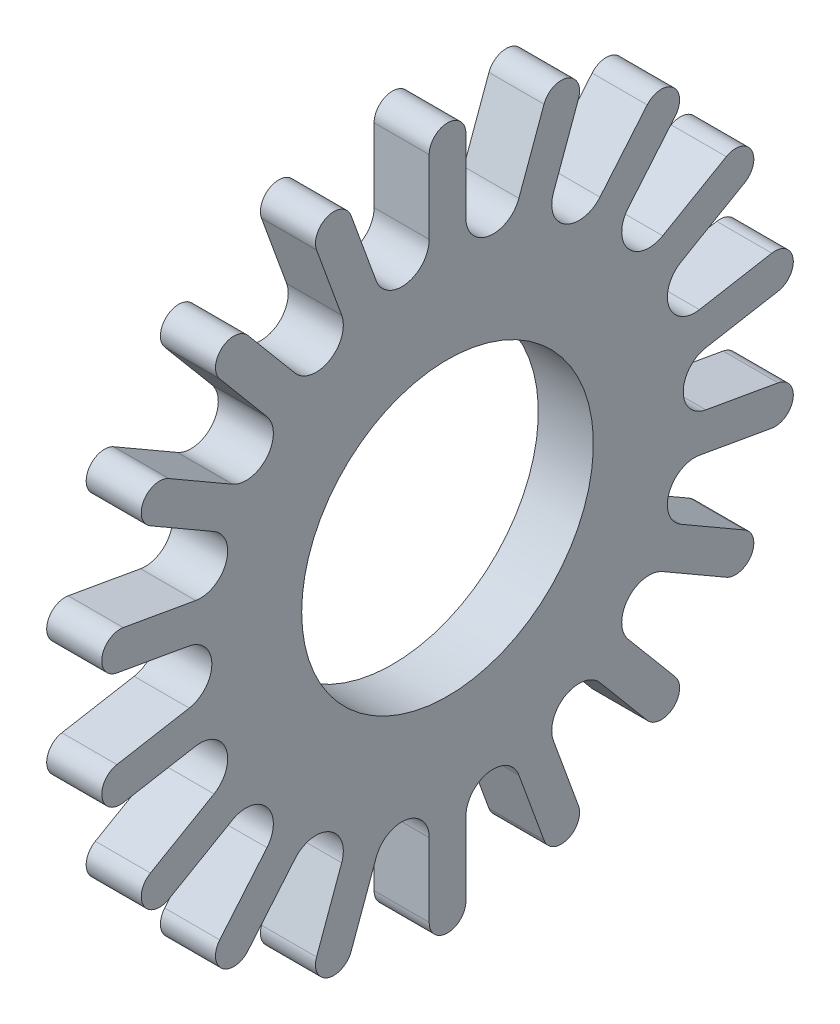
SolidWorks part; units mm, degrees
ref_plane "Front Plane" through (0, 0, 0) normal (0, 0, 1) x (1, 0, 0)
ref_plane "Top Plane" through (0, 0, 0) normal (0, 1, 0) x (1, 0, 0)
ref_plane "Right Plane" through (0, 0, 0) normal (1, 0, 0) x (0, 0, -1)
sketch "Sketch1" plane through (0, 0, 0) normal (1, 0, 0) x (0, 0, -1)
  line L0 (6.9829, 40.646) -> (4.811, 34.6789)
  line L1 (9.9664, 39.5601) -> (7.7946, 33.593)
  line L2 (-2.9472, 41.8371) -> (-2.9472, 35.4871)
  line L4 (0.2278, 41.8371) -> (0.2278, 35.4871)
  line L6 (15.9067, 36.1304) -> (11.825, 31.2661)
  line L7 (18.3389, 34.0896) -> (14.2572, 29.2252)
  line L9 (22.7479, 28.8351) -> (17.2486, 25.6601)
  line L10 (24.3354, 26.0855) -> (18.8361, 22.9105)
  line L12 (26.6814, 19.6399) -> (20.4279, 18.5372)
  line L13 (27.2327, 16.5131) -> (20.9792, 15.4105)
  line L15 (27.2327, 9.6539) -> (20.9792, 10.7565)
  line L16 (26.6814, 6.5271) -> (20.4279, 7.6298)
  line L18 (24.3354, 0.0815) -> (18.8361, 3.2565)
  line L19 (22.7479, -2.6681) -> (17.2486, 0.5069)
  line L21 (18.3389, -7.9226) -> (14.2572, -3.0582)
  line L22 (15.9067, -9.9635) -> (11.825, -5.0991)
  line L24 (9.9664, -13.3931) -> (7.7946, -7.426)
  line L25 (6.9829, -14.479) -> (4.811, -8.5119)
  line L27 (0.2278, -15.6701) -> (0.2278, -9.3201)
  line L28 (-2.9472, -15.6701) -> (-2.9472, -9.3201)
  line L30 (-9.7022, -14.479) -> (-7.5304, -8.5119)
  line L31 (-12.6858, -13.3931) -> (-10.5139, -7.426)
  line L33 (-18.626, -9.9635) -> (-14.5443, -5.0991)
  line L34 (-21.0582, -7.9226) -> (-16.9765, -3.0582)
  line L36 (-25.4673, -2.6681) -> (-19.968, 0.5069)
  line L37 (-27.0548, 0.0815) -> (-21.5555, 3.2565)
  line L39 (-29.4008, 6.5271) -> (-23.1472, 7.6298)
  line L40 (-29.9521, 9.6539) -> (-23.6986, 10.7565)
  line L42 (-29.9521, 16.5131) -> (-23.6986, 15.4105)
  line L43 (-29.4008, 19.6399) -> (-23.1472, 18.5372)
  line L45 (-27.0548, 26.0855) -> (-21.5555, 22.9105)
  line L46 (-25.4673, 28.8351) -> (-19.968, 25.6601)
  line L48 (-21.0582, 34.0896) -> (-16.9765, 29.2252)
  line L49 (-18.626, 36.1304) -> (-14.5443, 31.2661)
  line L51 (-12.6858, 39.5601) -> (-10.5139, 33.593)
  line L52 (-9.7022, 40.646) -> (-7.5304, 34.6789)
  line L54 (-17.7064, 25.7882) -> (-15.2742, 27.8291) [skipped]
  line L55 (-12.3753, 30.6129) -> (-9.3917, 31.6988) [skipped]
  line L56 (-5.7155, 33.3233) -> (-2.5405, 33.3233) [skipped]
  line L57 (1.4696, 33.5925) -> (4.4531, 32.5066) [skipped]
  line L58 (8.3135, 31.388) -> (10.7457, 29.3471) [skipped]
  line L59 (13.9906, 26.9757) -> (15.5781, 24.2261) [skipped]
  line L60 (17.8163, 20.8878) -> (18.3676, 17.761) [skipped]
  line L61 (19.329, 13.8585) -> (18.7777, 10.7318) [skipped]
  line L62 (18.3464, 6.7358) -> (16.7589, 3.9862) [skipped]
  line L63 (14.987, 0.3788) -> (12.5548, -1.6621) [skipped]
  line L64 (9.6559, -4.4459) -> (6.6724, -5.5319) [skipped]
  line L65 (2.9962, -7.1563) -> (-0.1788, -7.1563) [skipped]
  line L66 (-4.189, -7.4255) -> (-7.1725, -6.3396) [skipped]
  line L67 (-11.0328, -5.221) -> (-13.465, -3.1802) [skipped]
  line L68 (-16.71, -0.8087) -> (-18.2975, 1.9409) [skipped]
  line L69 (-20.5357, 5.2792) -> (-21.087, 8.406) [skipped]
  line L70 (-22.0484, 12.3084) -> (-21.4971, 15.4352) [skipped]
  line L71 (-21.0658, 19.4311) -> (-19.4783, 22.1808) [skipped]
  circle A0 centre (-1.3597, 13.0835) radius 30.3411 construction
  arc A1 (-2.9472, 41.8371) -> (0.2278, 41.8371) centre (-1.3597, 41.8371) cw
  arc A2 (6.9829, 40.646) -> (9.9664, 39.5601) centre (8.4746, 40.103) cw
  arc A3 (15.9067, 36.1304) -> (18.3389, 34.0896) centre (17.1228, 35.11) cw
  arc A4 (22.7479, 28.8351) -> (24.3354, 26.0855) centre (23.5416, 27.4603) cw
  arc A5 (26.6814, 19.6399) -> (27.2327, 16.5131) centre (26.9571, 18.0765) cw
  arc A6 (27.2327, 9.6539) -> (26.6814, 6.5271) centre (26.9571, 8.0905) cw
  arc A7 (24.3354, 0.0815) -> (22.7479, -2.6681) centre (23.5416, -1.2933) cw
  arc A8 (18.3389, -7.9226) -> (15.9067, -9.9635) centre (17.1228, -8.943) cw
  arc A9 (9.9664, -13.3931) -> (6.9829, -14.479) centre (8.4746, -13.936) cw
  arc A10 (0.2278, -15.6701) -> (-2.9472, -15.6701) centre (-1.3597, -15.6701) cw
  arc A11 (-9.7022, -14.479) -> (-12.6858, -13.3931) centre (-11.194, -13.936) cw
  arc A12 (-18.626, -9.9635) -> (-21.0582, -7.9226) centre (-19.8421, -8.943) cw
  arc A13 (-25.4673, -2.6681) -> (-27.0548, 0.0815) centre (-26.261, -1.2933) cw
  arc A14 (-29.4008, 6.5271) -> (-29.9521, 9.6539) centre (-29.6764, 8.0905) cw
  arc A15 (-29.9521, 16.5131) -> (-29.4008, 19.6399) centre (-29.6764, 18.0765) cw
  arc A16 (-27.0548, 26.0855) -> (-25.4673, 28.8351) centre (-26.261, 27.4603) cw
  arc A17 (-21.0582, 34.0896) -> (-18.626, 36.1304) centre (-19.8421, 35.11) cw
  arc A18 (-12.6858, 39.5601) -> (-9.7022, 40.646) centre (-11.194, 40.103) cw
  arc A19 (4.811, 34.6789) -> (0.2278, 35.4871) centre (2.5907, 35.4871) cw
  arc A20 (11.825, 31.2661) -> (7.7946, 33.593) centre (10.0149, 32.7849) cw
  arc A21 (17.2486, 25.6601) -> (14.2572, 29.2252) centre (16.0672, 27.7064) cw
  arc A22 (20.4279, 18.5372) -> (18.8361, 22.9105) centre (20.0176, 20.8642) cw
  arc A23 (20.9792, 10.7565) -> (20.9792, 15.4105) centre (21.3895, 13.0835) cw
  arc A24 (18.8361, 3.2565) -> (20.4279, 7.6298) centre (20.0176, 5.3028) cw
  arc A25 (14.2572, -3.0582) -> (17.2486, 0.5069) centre (16.0672, -1.5394) cw
  arc A26 (7.7946, -7.426) -> (11.825, -5.0991) centre (10.0149, -6.6179) cw
  arc A27 (0.2278, -9.3201) -> (4.811, -8.5119) centre (2.5907, -9.3201) cw
  arc A28 (-7.5304, -8.5119) -> (-2.9472, -9.3201) centre (-5.31, -9.3201) cw
  arc A29 (-14.5443, -5.0991) -> (-10.5139, -7.426) centre (-12.7343, -6.6179) cw
  arc A30 (-19.968, 0.5069) -> (-16.9765, -3.0582) centre (-18.7866, -1.5394) cw
  arc A31 (-23.1472, 7.6298) -> (-21.5555, 3.2565) centre (-22.7369, 5.3028) cw
  arc A32 (-23.6986, 15.4105) -> (-23.6986, 10.7565) centre (-24.1089, 13.0835) cw
  arc A33 (-21.5555, 22.9105) -> (-23.1472, 18.5372) centre (-22.7369, 20.8642) cw
  arc A34 (-16.9765, 29.2252) -> (-19.968, 25.6601) centre (-18.7866, 27.7064) cw
  arc A35 (-10.5139, 33.593) -> (-14.5443, 31.2661) centre (-12.7343, 32.7849) cw
  arc A36 (-2.9472, 35.4871) -> (-7.5304, 34.6789) centre (-5.31, 35.4871) cw
  circle A37 centre (-1.3597, 13.0835) radius 12.6145
  dimension "D1" = 18
  dimension "D2" = 3.175
  dimension "D3" = 6.35
  dimension "D4" = 18
extrude "Boss-Extrude1" add sketch "Sketch1" along normal blind 4.7625
